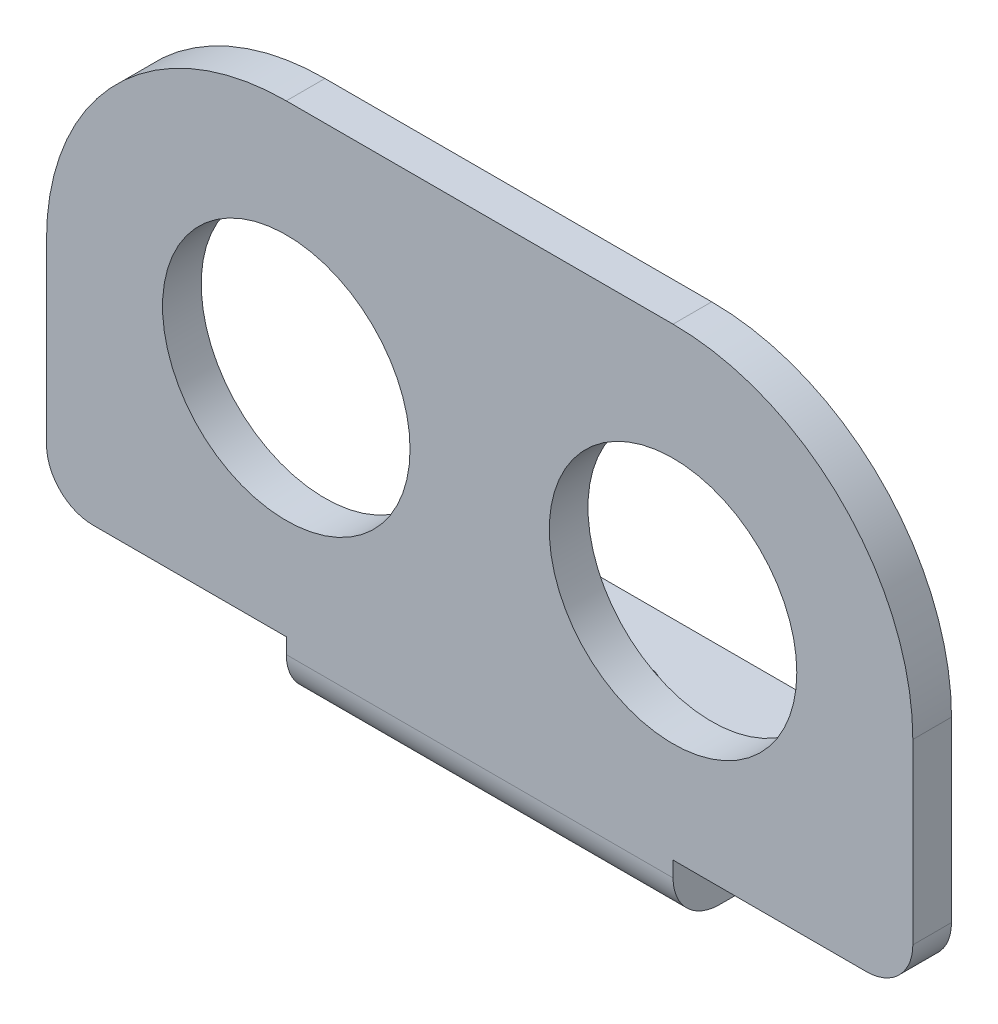
SolidWorks part; units mm, degrees
ref_plane "Front Plane" through (0, 0, 0) normal (0, 0, 1) x (1, 0, 0)
ref_plane "Top Plane" through (0, 0, 0) normal (0, 1, 0) x (1, 0, 0)
ref_plane "Right Plane" through (0, 0, 0) normal (1, 0, 0) x (0, 0, -1)
sketch "Sketch1" plane through (0, 0, 0) normal (0, 0, 1) x (1, 0, 0)
  line L0 (-12.5, -0.5) -> (12.5, -0.5) construction
  line L1 (-28, 15) -> (28, 15) construction
  line L2 (-28, 15) -> (-28, -15) construction
  line L3 (-28, -15) -> (28, -15) construction
  line L4 (28, 15) -> (28, -15) construction
  line L5 (-28, 15) -> (28, -15) construction
  line L6 (-28, -15) -> (28, 15) construction
  line L7 (-28, -15) -> (-28, -0.5)
  line L8 (12.5, 15) -> (-12.5, 15)
  line L9 (28, -0.5) -> (28, -15)
  line L10 (-28, -15) -> (-12.5, -15)
  line L11 (-12.5, -15) -> (12.5, -15) construction
  line L12 (-12.5, -15) -> (-12.5, -19)
  line L13 (-12.5, -19) -> (12.5, -19)
  line L14 (12.5, -15) -> (12.5, -19)
  line L15 (12.5, -15) -> (28, -15)
  circle A0 centre (12.5, -0.5) radius 8
  circle A1 centre (-12.5, -0.5) radius 8
  arc A2 (-12.5, 15) -> (-28, -0.5) centre (-12.5, -0.5) ccw
  arc A3 (12.5, 15) -> (28, -0.5) centre (12.5, -0.5) cw
  point P0 (0, 0)
  point P18 (0, -15)
  dimension "D2" = 16
  dimension "D5" = 25
  dimension "D1" = 25
  dimension "D3" = 56
  dimension "D4" = 30
  dimension "D6" = 4
extrude "Boss-Extrude1" add sketch "Sketch1" along normal blind 2.5
fillet "Fillet1" radius 3 2 edges at (-28, -15, 1.25) (28, -15, 1.25)
sketch "Sketch2" plane through (0, 0, 0) normal (0, 0, -1) x (-1, 0, 0)
  line L0 (12.5, -15) -> (12.5, -19) construction
  line L1 (-12.5, -19) -> (12.5, -19)
  line L2 (-12.5, -19) -> (-12.5, -16)
  line L3 (-12.5, -16) -> (12.5, -16)
  line L4 (12.5, -19) -> (12.5, -16)
  dimension "D1" = 3
extrude "Boss-Extrude2" add sketch "Sketch2" along normal blind 12
fillet "Fillet2" radius 2.5 2 edges at (-12.5, -17.5, -12) (12.5, -17.5, -12)
fillet "Fillet3" radius 3 1 edges at (0, -19, 2.5)
sketch "Sketch3" plane through (0, -16, 0) normal (0, 1, 0) x (1, 0, 0)
  line L0 (-12.5, 7) -> (12.5, 7) construction
  line L1 (-12.5, 9.5) -> (-12.5, 0) construction
  line L2 (12.5, 9.5) -> (12.5, 0) construction
  line L3 (-10, 12) -> (10, 12) construction
  circle A0 centre (0, 7) radius 1.5
  point P9 (0, 7)
  dimension "D1" = 3
  dimension "D2" = 5
extrude "Cut-Extrude1" cut sketch "Sketch3" against normal through all
